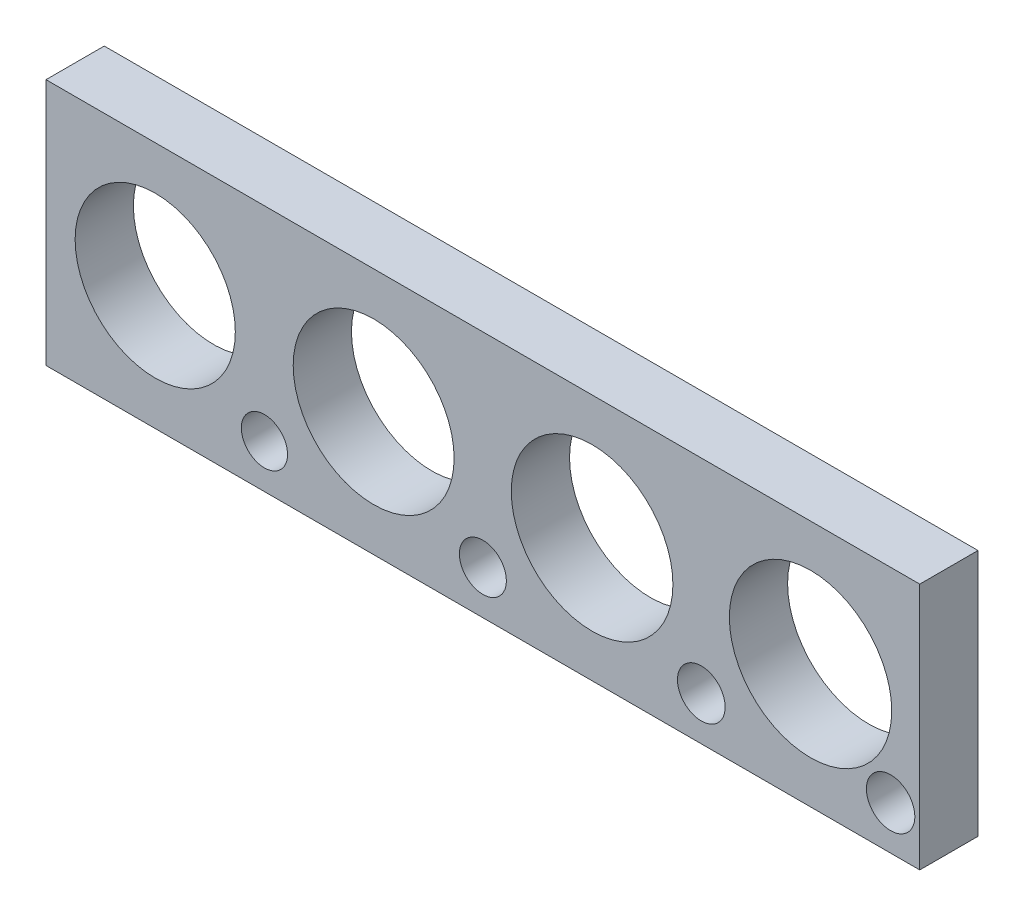
SolidWorks part; units mm, degrees
ref_plane "Front Plane" through (0, 0, 0) normal (0, 0, 1) x (1, 0, 0)
ref_plane "Top Plane" through (0, 0, 0) normal (0, 1, 0) x (1, 0, 0)
ref_plane "Right Plane" through (0, 0, 0) normal (1, 0, 0) x (0, 0, -1)
sketch "Coupon_plate_profile" plane through (0, 0, 0) normal (0, 0, 1) x (1, 0, 0)
  line L1 (-60, -17) -> (60, -17)
  line L2 (-60, -17) -> (-60, 17)
  line L3 (-60, 17) -> (60, 17)
  line L4 (60, -17) -> (60, 17)
  dimension "D1" = 120
  dimension "D2" = 34
extrude "Coupon_plate" add sketch "Coupon_plate_profile" along normal blind 8
sketch "Bearing_seat_trial_22p0_22p1_22p2_22p3" plane through (0, 0, 0) normal (0, 0, 1) x (1, 0, 0)
  circle A0 centre (-45, 0) radius 11
  circle A1 centre (-15, 0) radius 11.05
  circle A2 centre (15, 0) radius 11.1
  circle A3 centre (45, 0) radius 11.15
  dimension "D1" = 22
  dimension "D2" = 22.1
  dimension "D3" = 22.2
  dimension "D4" = 22.3
extrude "Bearing_fit_trial_through" cut sketch "Bearing_seat_trial_22p0_22p1_22p2_22p3" along normal through all from offset 1
sketch "Dowel_trial_6p35_6p45_6p55_6p65" plane through (0, 0, 0) normal (0, 0, 1) x (1, 0, 0)
  circle A0 centre (-30, -11) radius 3.175
  circle A1 centre (0, -11) radius 3.225
  circle A2 centre (30, -11) radius 3.275
  circle A3 centre (56, -11) radius 3.325
  dimension "D1" = 6.35
  dimension "D2" = 6.45
  dimension "D3" = 6.55
  dimension "D4" = 6.65
extrude "Dowel_fit_trial_through" cut sketch "Dowel_trial_6p35_6p45_6p55_6p65" along normal through all from offset 1
